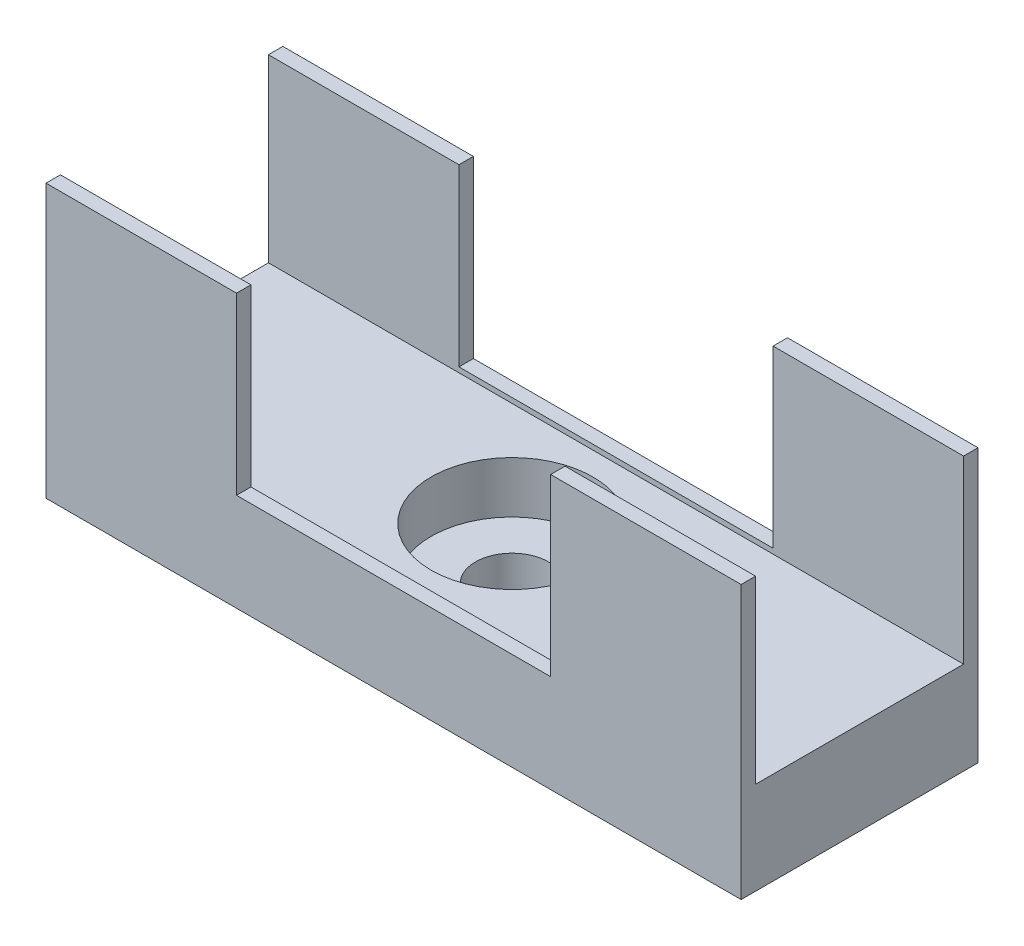
SolidWorks part; units mm, degrees
ref_plane "Front Plane" through (0, 0, 0) normal (0, 0, 1) x (1, 0, 0)
ref_plane "Top Plane" through (0, 0, 0) normal (0, 1, 0) x (1, 0, 0)
ref_plane "Right Plane" through (0, 0, 0) normal (1, 0, 0) x (0, 0, -1)
sketch "Sketch1" plane through (0, 0, 0) normal (0, 1, 0) x (1, 0, 0)
  line L1 (-17.145, 5.842) -> (17.145, 5.842)
  line L2 (-17.145, 5.842) -> (-17.145, -5.842)
  line L3 (-17.145, -5.842) -> (17.145, -5.842)
  line L4 (17.145, 5.842) -> (17.145, -5.842)
  line L5 (-17.145, 5.842) -> (17.145, -5.842) construction
  line L6 (-17.145, -5.842) -> (17.145, 5.842) construction
  point P0 (0, 0)
  dimension "D1" = 34.29
  dimension "D2" = 11.684
extrude "Boss-Extrude1" add sketch "Sketch1" along normal blind 13.462
sketch "Sketch3" plane through (0, 0, 5.842) normal (0, 0, 1) x (1, 0, 0)
  line L0 (-17.145, 0) -> (17.145, 0) construction
  line L1 (-7.747, 13.462) -> (7.747, 13.462)
  line L2 (-7.747, 13.462) -> (-7.747, 4.826)
  line L3 (-7.747, 4.826) -> (7.747, 4.826)
  line L4 (7.747, 13.462) -> (7.747, 4.826)
  line L5 (-17.145, 13.462) -> (17.145, 13.462) construction
  line L6 (17.145, 13.462) -> (17.145, 0) construction
  dimension "D1" = 4.826
  dimension "D2" = 15.494
  dimension "D3" = 9.398
extrude "Cut-Extrude1" cut sketch "Sketch3" against normal blind 23.622
sketch "Sketch4" plane through (0, 13.462, 0) normal (0, 1, 0) x (1, 0, 0)
  line L0 (17.145, -5.842) -> (17.145, 5.842) construction
  line L1 (-17.145, 5.1308) -> (17.145, 5.1308)
  line L2 (-17.145, 5.1308) -> (-17.145, -5.1308)
  line L3 (-17.145, -5.1308) -> (17.145, -5.1308)
  line L4 (17.145, 5.1308) -> (17.145, -5.1308)
  line L5 (-17.145, 5.1308) -> (17.145, -5.1308) construction
  line L6 (-17.145, -5.1308) -> (17.145, 5.1308) construction
  point P0 (0, 0)
  dimension "D1" = 10.2616
extrude "Cut-Extrude2" cut sketch "Sketch4" against normal blind 8.89
sketch "Sketch5" plane through (0, 4.572, 0) normal (0, 1, 0) x (1, 0, 0)
  circle A0 centre (0, 0) radius 3.9878
  dimension "D1" = 7.9756
extrude "Cut-Extrude3" cut sketch "Sketch5" against normal blind 2.54
sketch "Sketch6" plane through (0, 2.032, 0) normal (0, 1, 0) x (1, 0, 0)
  circle A0 centre (0, 0) radius 1.8034
  dimension "D1" = 3.6068
extrude "Cut-Extrude4" cut sketch "Sketch6" against normal blind 7.62
